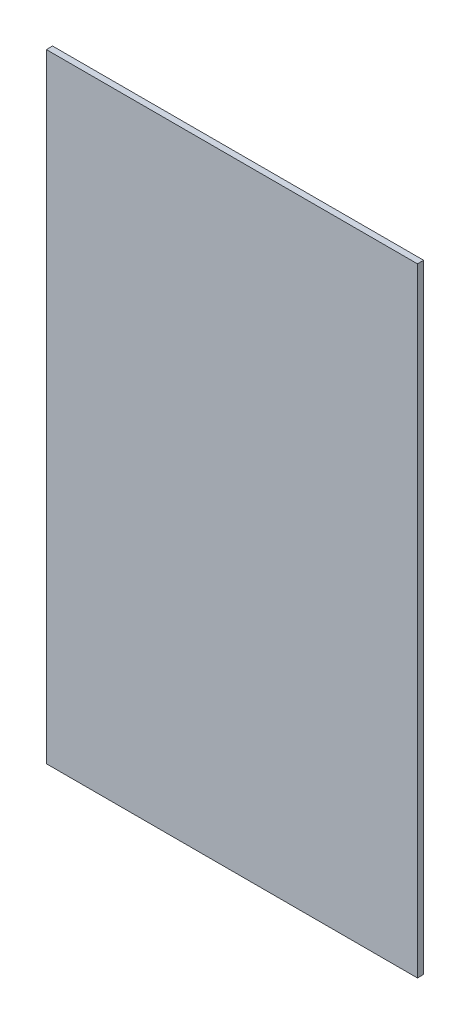
SolidWorks part; units mm, degrees
ref_plane "Front Plane" through (0, 0, 0) normal (0, 0, 1) x (1, 0, 0)
ref_plane "Top Plane" through (0, 0, 0) normal (0, 1, 0) x (1, 0, 0)
ref_plane "Right Plane" through (0, 0, 0) normal (1, 0, 0) x (0, 0, -1)
sketch "Sketch1" plane through (0, 0, 0) normal (0, 0, 1) x (1, 0, 0)
  line L1 (0, 0) -> (152.4, 0)
  line L2 (0, 0) -> (0, -254)
  line L3 (0, -254) -> (152.4, -254)
  line L4 (152.4, 0) -> (152.4, -254)
extrude "Boss-Extrude1" add sketch "Sketch1" along normal blind 2.54
